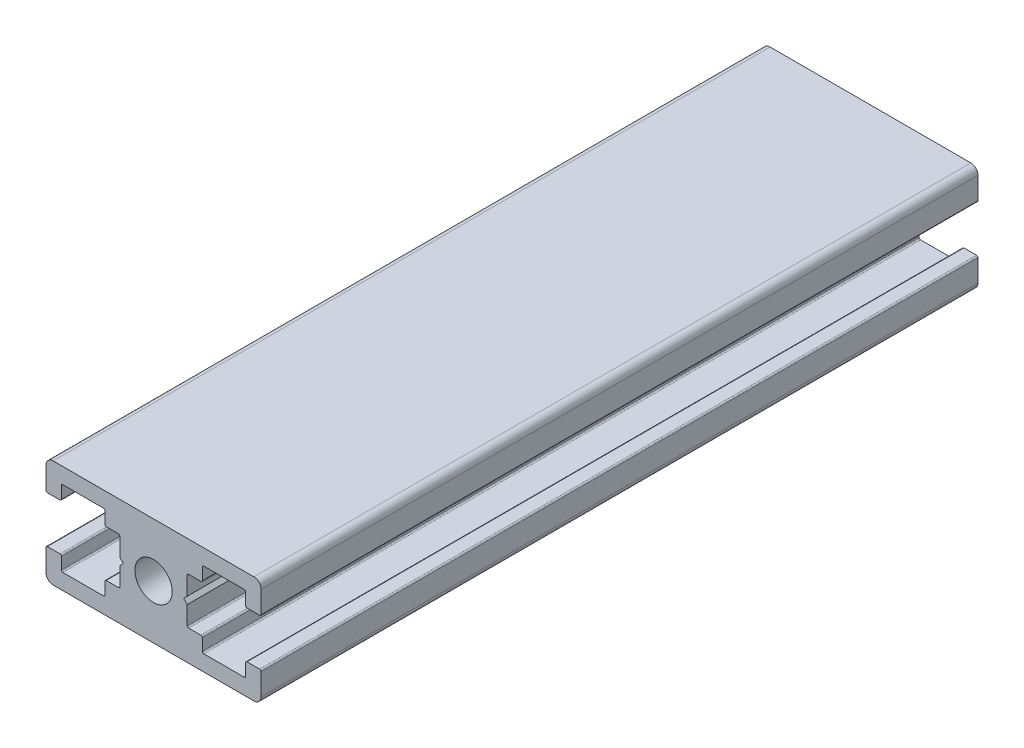
SolidWorks part; units mm, degrees
ref_plane "前视基准面" through (0, 0, 0) normal (0, 0, 1) x (1, 0, 0)
ref_plane "上视基准面" through (0, 0, 0) normal (0, 1, 0) x (1, 0, 0)
ref_plane "右视基准面" through (0, 0, 0) normal (1, 0, 0) x (0, 0, -1)
sketch "草图1" plane through (0, 0, 0) normal (0, 0, 1) x (1, 0, 0)
  line B0 (-4.7, 0.5) -> (-4.2, 0)
  line B1 (-4.2, 0) -> (-4.7, -0.5)
  line B2 (-4.7, -0.5) -> (-4.7, -3.05)
  line B3 (-4.9, -3.25) -> (-6.6, -3.25)
  line B4 (-6.8, -3.45) -> (-6.8, -5.1)
  line B5 (-7, -5.3) -> (-12.65, -5.3)
  line B6 (-12.85, -5.1) -> (-12.85, -3.45)
  line B7 (-13.05, -3.25) -> (-14.8, -3.25)
  line B8 (-15, -3.45) -> (-15, -6.5)
  line B9 (-14, -7.5) -> (14, -7.5)
  line B10 (15, -6.5) -> (15, -3.45)
  line B11 (14.8, -3.25) -> (13.05, -3.25)
  line B12 (12.85, -3.45) -> (12.85, -5.1)
  line B13 (12.65, -5.3) -> (7, -5.3)
  line B14 (6.8, -5.1) -> (6.8, -3.45)
  line B15 (6.6, -3.25) -> (4.9, -3.25)
  line B16 (4.7, -3.05) -> (4.7, -0.5)
  line B17 (4.7, -0.5) -> (4.2, 0)
  line B18 (4.2, 0) -> (4.7, 0.5)
  line B19 (4.7, 0.5) -> (4.7, 3.05)
  line B20 (4.9, 3.25) -> (6.6, 3.25)
  line B21 (6.8, 3.45) -> (6.8, 5.1)
  line B22 (7, 5.3) -> (12.65, 5.3)
  line B23 (12.85, 5.1) -> (12.85, 3.45)
  line B24 (13.05, 3.25) -> (14.8, 3.25)
  line B25 (15, 3.45) -> (15, 6.5)
  line B26 (14, 7.5) -> (-14, 7.5)
  line B27 (-15, 6.5) -> (-15, 3.45)
  line B28 (-14.8, 3.25) -> (-13.05, 3.25)
  line B29 (-12.85, 3.45) -> (-12.85, 5.1)
  line B30 (-12.65, 5.3) -> (-7, 5.3)
  line B31 (-6.8, 5.1) -> (-6.8, 3.45)
  line B32 (-6.6, 3.25) -> (-4.9, 3.25)
  line B33 (-4.7, 3.05) -> (-4.7, 0.5)
  arc B34 (-4.9, -3.25) -> (-4.7, -3.05) centre (-4.9, -3.05) ccw
  arc B35 (-6.6, -3.25) -> (-6.8, -3.45) centre (-6.6, -3.45) ccw
  arc B36 (-7, -5.3) -> (-6.8, -5.1) centre (-7, -5.1) ccw
  arc B37 (-12.85, -5.1) -> (-12.65, -5.3) centre (-12.65, -5.1) ccw
  arc B38 (-12.85, -3.45) -> (-13.05, -3.25) centre (-13.05, -3.45) ccw
  arc B39 (-14.8, -3.25) -> (-15, -3.45) centre (-14.8, -3.45) ccw
  arc B40 (-15, -6.5) -> (-14, -7.5) centre (-14, -6.5) ccw
  arc B41 (14, -7.5) -> (15, -6.5) centre (14, -6.5) ccw
  arc B42 (15, -3.45) -> (14.8, -3.25) centre (14.8, -3.45) ccw
  arc B43 (13.05, -3.25) -> (12.85, -3.45) centre (13.05, -3.45) ccw
  arc B44 (12.65, -5.3) -> (12.85, -5.1) centre (12.65, -5.1) ccw
  arc B45 (6.8, -5.1) -> (7, -5.3) centre (7, -5.1) ccw
  arc B46 (6.8, -3.45) -> (6.6, -3.25) centre (6.6, -3.45) ccw
  arc B47 (4.7, -3.05) -> (4.9, -3.25) centre (4.9, -3.05) ccw
  arc B48 (4.9, 3.25) -> (4.7, 3.05) centre (4.9, 3.05) ccw
  arc B49 (6.6, 3.25) -> (6.8, 3.45) centre (6.6, 3.45) ccw
  arc B50 (7, 5.3) -> (6.8, 5.1) centre (7, 5.1) ccw
  arc B51 (12.85, 5.1) -> (12.65, 5.3) centre (12.65, 5.1) ccw
  arc B52 (12.85, 3.45) -> (13.05, 3.25) centre (13.05, 3.45) ccw
  arc B53 (14.8, 3.25) -> (15, 3.45) centre (14.8, 3.45) ccw
  arc B54 (15, 6.5) -> (14, 7.5) centre (14, 6.5) ccw
  arc B55 (-14, 7.5) -> (-15, 6.5) centre (-14, 6.5) ccw
  arc B56 (-15, 3.45) -> (-14.8, 3.25) centre (-14.8, 3.45) ccw
  arc B57 (-13.05, 3.25) -> (-12.85, 3.45) centre (-13.05, 3.45) ccw
  arc B58 (-12.65, 5.3) -> (-12.85, 5.1) centre (-12.65, 5.1) ccw
  arc B59 (-6.8, 5.1) -> (-7, 5.3) centre (-7, 5.1) ccw
  arc B60 (-6.8, 3.45) -> (-6.6, 3.25) centre (-6.6, 3.45) ccw
  arc B61 (-4.7, 3.05) -> (-4.9, 3.25) centre (-4.9, 3.05) ccw
  circle B62 centre (0, 0) radius 2.6
sketch_block_instance "A$C7EEA2D4A-1"
sketch_block "A$C7EEA2D4A"
extrude "凸台-拉伸1" add sketch "草图1" along normal blind 100
